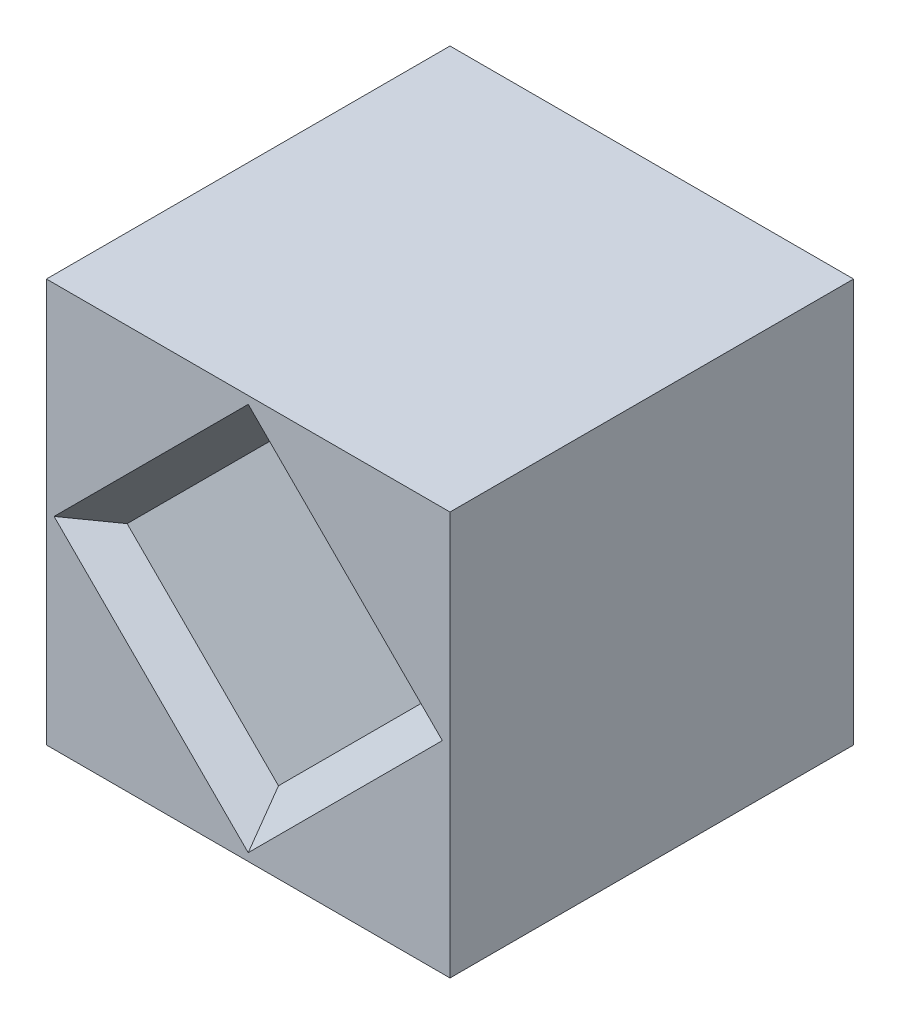
SolidWorks part; units mm, degrees
ref_plane "Front Plane" through (0, 0, 0) normal (0, 0, 1) x (1, 0, 0)
ref_plane "Top Plane" through (0, 0, 0) normal (0, 1, 0) x (1, 0, 0)
ref_plane "Right Plane" through (0, 0, 0) normal (1, 0, 0) x (0, 0, -1)
sketch "Sketch1" plane through (0, 0, 0) normal (0, 1, 0) x (1, 0, 0)
  line L1 (0, 0) -> (8.4667, 0)
  line L2 (0, 0) -> (0, 8.4667)
  line L3 (0, 8.4667) -> (8.4667, 8.4667)
  line L4 (8.4667, 0) -> (8.4667, 8.4667)
  dimension "D1" = 8.4667
extrude "Boss-Extrude1" add sketch "Sketch1" along normal blind 8.4667
sketch "Sketch3" plane through (0, 0, 0) normal (0, 0, 1) x (1, 0, 0)
  line L0 (1.0583, 4.2333) -> (4.2333, 1.0583)
  line L1 (1.0583, 4.2333) -> (4.2333, 7.4083)
  line L2 (4.2333, 1.0583) -> (7.4083, 4.2333)
  line L3 (4.2333, 7.4083) -> (7.4083, 4.2333)
  line L4 (1.0583, 4.2333) -> (7.4083, 4.2333) construction
  line L5 (4.2333, 1.0583) -> (4.2333, 7.4083) construction
  line L6 (8.4667, 8.4667) -> (8.4667, 0) construction
  line L7 (0, 8.4667) -> (8.4667, 8.4667) construction
  point P1 (4.2333, 4.2333)
  point P3 (8.4667, 4.2333)
  point P10 (4.2333, 8.4667)
  dimension "D1" = 6.35
extrude "Cut-Extrude1" cut sketch "Sketch3" against normal blind 6.35
chamfer "Chamfer1" distance 0.635 angle 45 8 edges at (5.8208, 5.8208, -6.35) (5.8208, 2.6458, -6.35) (2.6458, 2.6458, -6.35) (2.6458, 5.8208, -6.35) (5.8208, 5.8208, 0) (5.8208, 2.6458, 0) (2.6458, 2.6458, 0) (2.6458, 5.8208, 0)
